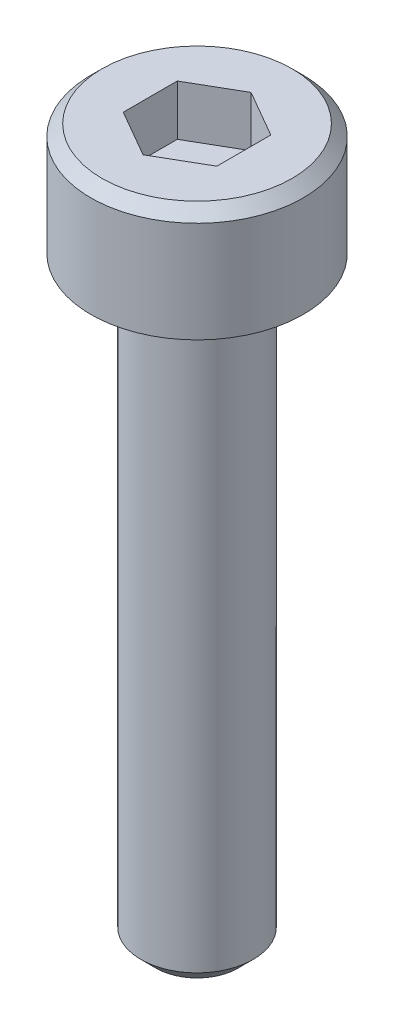
SolidWorks part; units mm, degrees
ref_plane "Front Plane" through (0, 0, 0) normal (0, 0, 1) x (1, 0, 0)
ref_plane "Top Plane" through (0, 0, 0) normal (0, 1, 0) x (1, 0, 0)
ref_plane "Right Plane" through (0, 0, 0) normal (1, 0, 0) x (0, 0, -1)
sketch "Sketch1" plane through (0, 0, 0) normal (0, 0, 1) x (1, 0, 0)
  line L0 (0, -16) -> (1.1, -16)
  line L1 (1.1, -16) -> (1.5, -15.6)
  line L2 (1.5, -15.6) -> (1.5, 0)
  line L3 (1.5, 0) -> (2.84, 0)
  line L4 (2.84, 0) -> (2.84, 2.7)
  line L5 (2.84, 2.7) -> (2.54, 3)
  line L6 (2.54, 3) -> (0, 3)
  line L7 (0, 3) -> (0, -16)
  line L8 (0, -10) -> (0, 1000) construction
revolve "Revolve1" add sketch "Sketch1" angle 360 about L8
cosmetic thread "Cosmetic Thread1" parameters "D1"=15.6, "D2"=2.4588
ref_plane "Plane1" through (0, 3, 0) normal (0, 1, 0) x (1, 0, 0)
sketch "Sketch2" plane through (0, 3, 0) normal (0, 1, 0) x (1, 0, 0)
  line L0 (1.25, -0.7217) -> (0, -1.4434)
  line L1 (0, -1.4434) -> (-1.25, -0.7217)
  line L2 (-1.25, -0.7217) -> (-1.25, 0.7217)
  line L3 (-1.25, 0.7217) -> (0, 1.4434)
  line L4 (0, 1.4434) -> (1.25, 0.7217)
  line L5 (1.25, 0.7217) -> (1.25, -0.7217)
extrude "Cut-Extrude1" cut sketch "Sketch2" against normal blind 1.35
